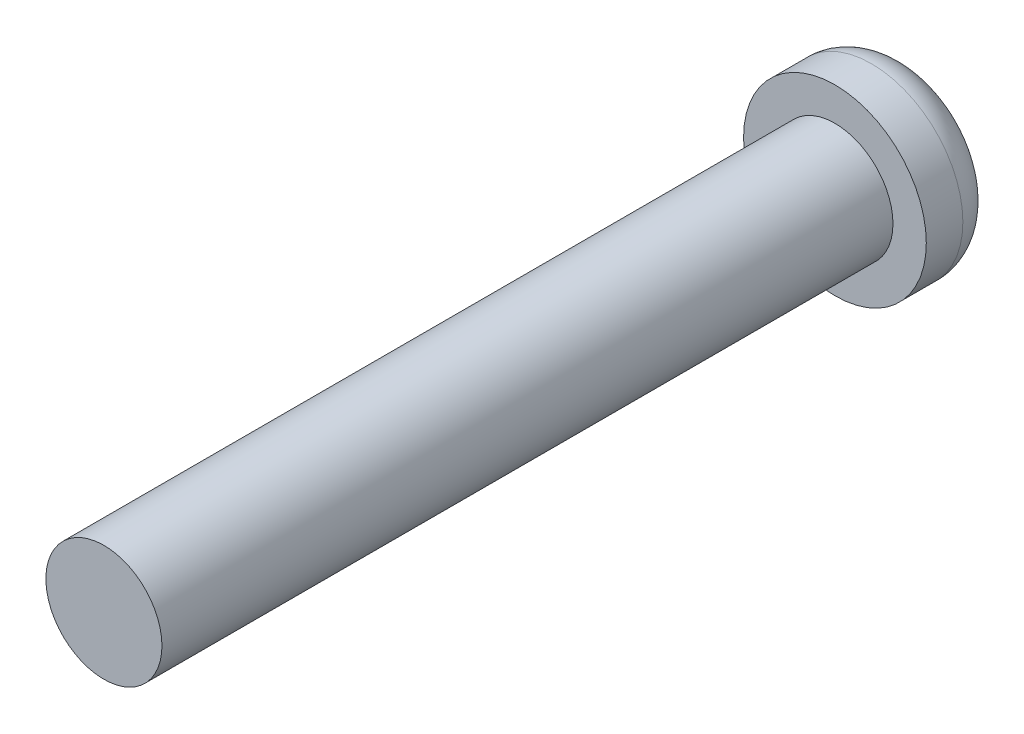
SolidWorks part; units mm, degrees
ref_plane "Alzado" through (0, 0, 0) normal (0, 0, 1) x (1, 0, 0)
ref_plane "Planta" through (0, 0, 0) normal (0, 1, 0) x (1, 0, 0)
ref_plane "Vista lateral" through (0, 0, 0) normal (1, 0, 0) x (0, 0, -1)
sketch "Croquis1" plane through (0, 0, 0) normal (0, 0, 1) x (1, 0, 0)
  circle A0 centre (0, 0) radius 1.5875
  dimension "D1" = 3.175
extrude "Saliente-Extruir1" add sketch "Croquis1" along normal blind 20
sketch "Croquis2" plane through (0, 0, 0) normal (0, 0, -1) x (-1, 0, 0)
  circle A0 centre (0, 0) radius 2.5
  dimension "D1" = 5
extrude "Saliente-Extruir2" add sketch "Croquis2" along normal blind 2
fillet "Redondeo2" radius 1 1 edges at (-2.5, 0, -2)
